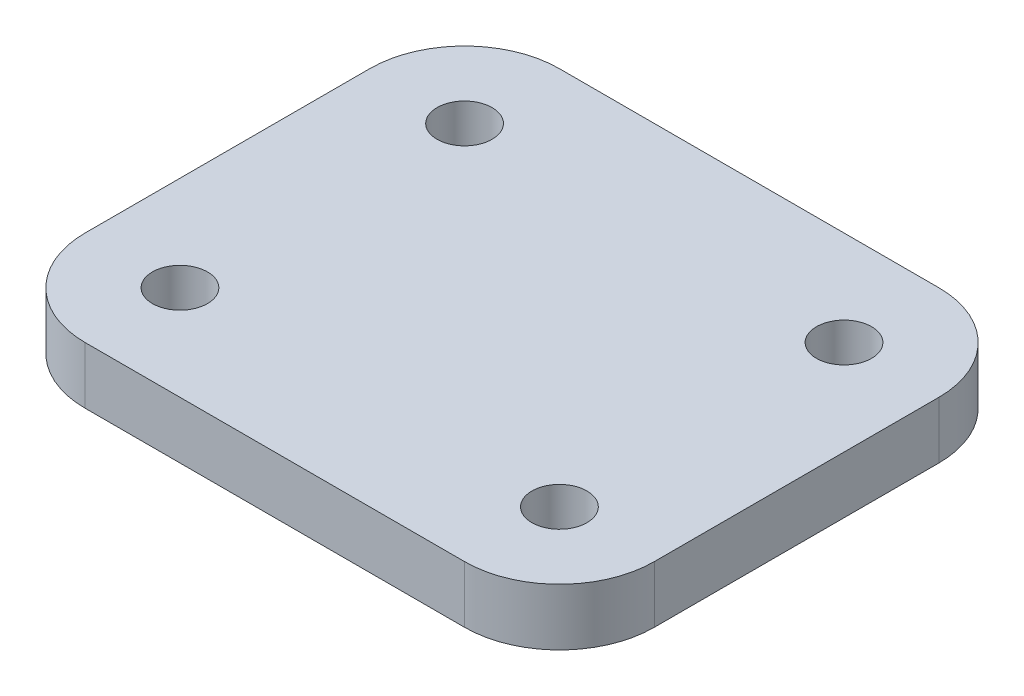
SolidWorks part; units mm, degrees
material "Thornel Mat VMA"
ref_plane "前视基准面" through (0, 0, 0) normal (0, 0, 1) x (1, 0, 0)
ref_plane "上视基准面" through (0, 0, 0) normal (0, 1, 0) x (1, 0, 0)
ref_plane "右视基准面" through (0, 0, 0) normal (1, 0, 0) x (0, 0, -1)
other "Configuration Table"
sketch "草图1" plane through (0, 0, 0) normal (0, 1, 0) x (1, 0, 0)
  line L1 (-15, -12.5) -> (15, -12.5)
  line L2 (-15, -12.5) -> (-15, 12.5)
  line L3 (-15, 12.5) -> (15, 12.5)
  line L4 (15, -12.5) -> (15, 12.5)
  line L5 (-15, -12.5) -> (15, 12.5) construction
  line L6 (-15, 12.5) -> (15, -12.5) construction
  line L7 (-10, -7.5) -> (10, -7.5) construction
  line L8 (-10, -7.5) -> (-10, 7.5) construction
  line L9 (-10, 7.5) -> (10, 7.5) construction
  line L10 (10, -7.5) -> (10, 7.5) construction
  line L11 (-10, -7.5) -> (10, 7.5) construction
  line L12 (-10, 7.5) -> (10, -7.5) construction
  circle A0 centre (-10, 7.5) radius 1.45
  circle A2 centre (-10, -7.5) radius 1.45
  circle A3 centre (10, -7.5) radius 1.45
  circle A4 centre (10, 7.5) radius 1.45
  point P0 (0, 0)
  point P6 (0, 0)
  dimension "D5" = 2.9
  dimension "D1" = 30
  dimension "D2" = 25
  dimension "D3" = 20
  dimension "D4" = 15
extrude "凸台-拉伸1" add sketch "草图1" along normal blind 3
fillet "圆角1" radius 5 4 edges at (-15, 1.5, 12.5) (-15, 1.5, -12.5) (15, 1.5, -12.5) (15, 1.5, 12.5)
sketch "草图2" plane through (0, 3, 0) normal (0, 1, 0) x (1, 0, 0)
  line L1 (-6, -5) -> (6, -5)
  line L2 (-6, -5) -> (-6, 5)
  line L3 (-6, 5) -> (6, 5)
  line L4 (6, -5) -> (6, 5)
  line L5 (-6, -5) -> (6, 5) construction
  line L6 (-6, 5) -> (6, -5) construction
  point P0 (0, 0)
  dimension "D1" = 12
  dimension "D2" = 10
extrude "切除-拉伸1" [suppressed] cut sketch "草图2" against normal through all
fillet "圆角2" [suppressed] radius 3
